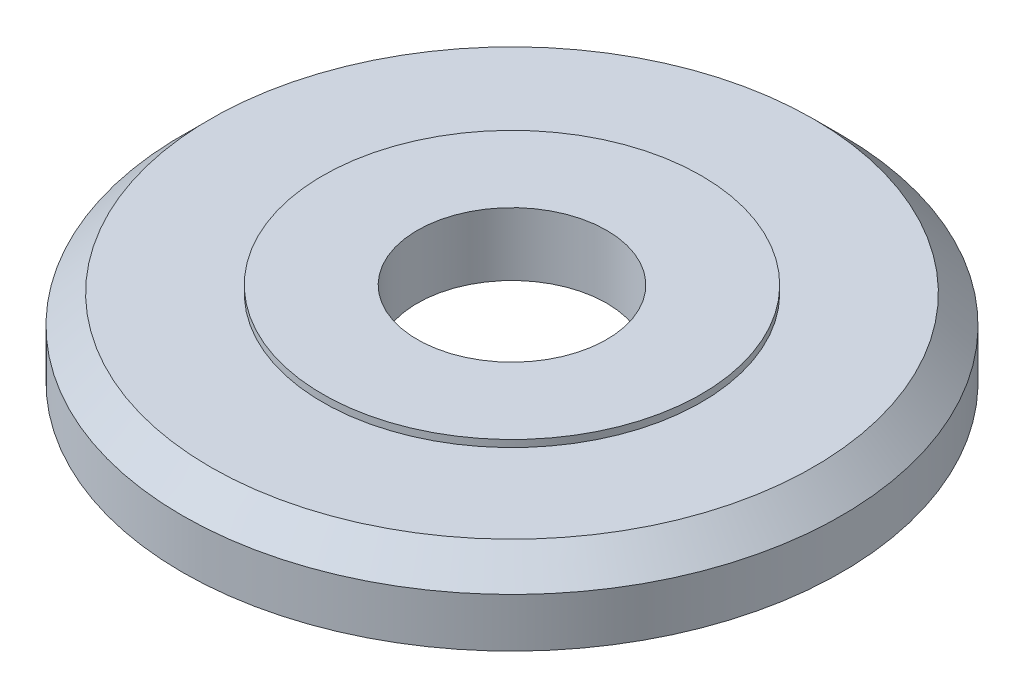
SolidWorks part; units mm, degrees
ref_plane "Плоскость1" through (0, 0, 0) normal (0, 0, 1) x (1, 0, 0)
ref_plane "Плоскость2" through (0, 0, 0) normal (0, 1, 0) x (1, 0, 0)
ref_plane "Плоскость3" through (0, 0, 0) normal (1, 0, 0) x (0, 0, -1)
sketch "Эскиз1" plane through (0, 0, 0) normal (0, 0, 1) x (1, 0, 0)
  line L0 (0, 3.397) -> (0, 73.6023) construction
  line L1 (13.5, 0) -> (13.5, 9)
  line L2 (13.5, 0) -> (36, 0)
  line L3 (36, 0) -> (37, -2)
  line L4 (37, -2) -> (39, -2)
  line L5 (39, -2) -> (39, 1)
  line L6 (39, 1) -> (45, 1)
  line L7 (45, 1) -> (45, -3)
  line L8 (45, -3) -> (47, -3)
  line L9 (47, -3) -> (47, 4)
  line L10 (47, 4) -> (43, 8)
  line L11 (43, 8) -> (27, 8)
  line L12 (27, 8) -> (27, 9)
  line L13 (27, 9) -> (13.5, 9)
  dimension "D1" = 27
  dimension "D2" = 74
  dimension "D3" = 72
  dimension "D4" = 2
  dimension "D5" = 94
  dimension "D6" = 78
  dimension "D7" = 90
  dimension "D8" = 4
  dimension "D9" = 1
  dimension "D10" = 1
  dimension "D11" = 54
  dimension "D12" = 12
  dimension "D13" = 7
  dimension "D14" = 86
revolve "Повернуть1" add sketch "Эскиз1" angle 360 about L0
